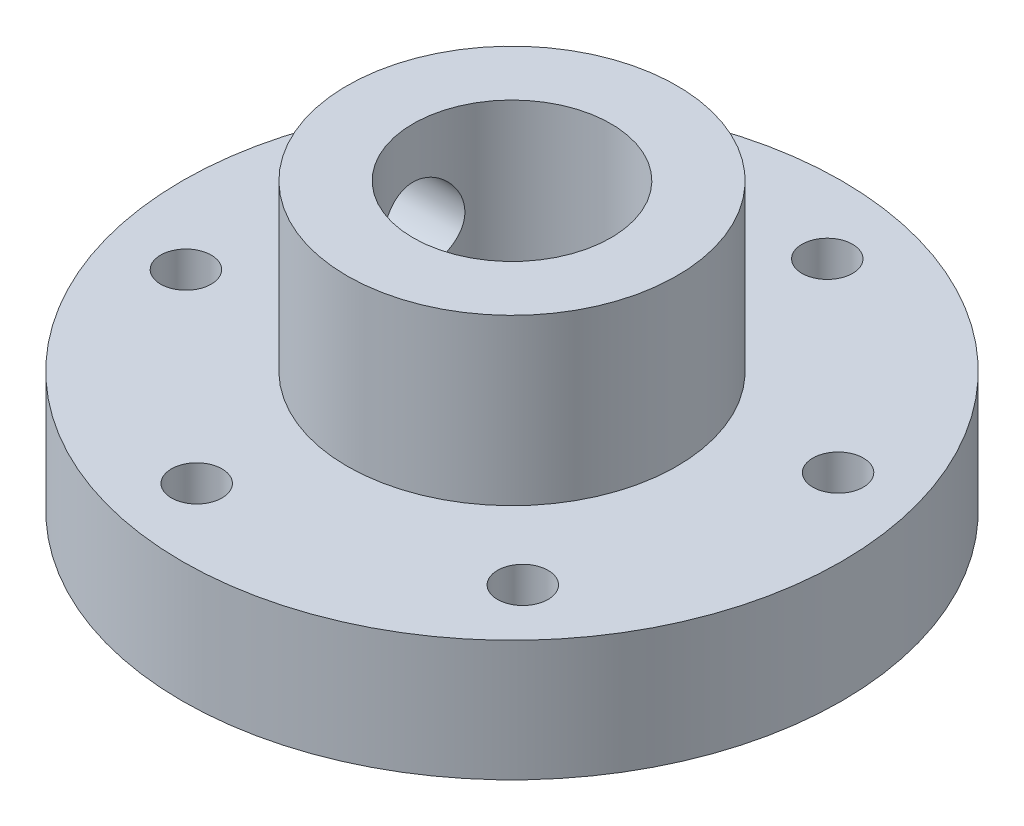
SolidWorks part; units mm, degrees
ref_plane "Front Plane" through (0, 0, 0) normal (0, 0, 1) x (1, 0, 0)
ref_plane "Top Plane" through (0, 0, 0) normal (0, 1, 0) x (1, 0, 0)
ref_plane "Right Plane" through (0, 0, 0) normal (1, 0, 0) x (0, 0, -1)
sketch "Sketch1" plane through (0, 0, 0) normal (0, 1, 0) x (1, 0, 0)
  circle A0 centre (0, 0) radius 30
  dimension "D1" = 60
sketch "Sketch2" plane through (0, 0, 0) normal (0, 1, 0) x (1, 0, 0)
  circle A0 centre (0, 0) radius 15
  dimension "D1" = 30
extrude "Boss-Extrude1" add sketch "Sketch2" along normal blind 26 contours A0
extrude "Boss-Extrude2" add sketch "Sketch1" along normal blind 11 contours A0
sketch "Sketch3" plane through (0, 26, 0) normal (0, 1, 0) x (1, 0, 0)
  circle A0 centre (0, 0) radius 9
  dimension "D1" = 18
extrude "Cut-Extrude1" cut sketch "Sketch3" against normal through all
sketch "Sketch4" plane through (0, 11, 0) normal (0, 1, 0) x (1, 0, 0)
  circle A0 centre (5.495, 23.1924) radius 2.3
  dimension "D1" = 4.6
sketch "Sketch6" plane through (0, 11, 0) normal (0, 1, 0) x (1, 0, 0)
  line L0 (-30, 0) -> (30, 0) construction
  circle A0 centre (0, 0) radius 30 construction
extrude "Cut-Extrude2" cut sketch "Sketch4" against normal through all
pattern_circular "CirPattern1" count 6 over 360 about axis through (0, 0, 0) along (0, 1, 0) of "Cut-Extrude2"
sketch "Sketch7" plane through (0, 0, 0) normal (1, 0, 0) x (0, 0, -1)
  line L0 (15, 26) -> (-15, 26) construction
  circle A0 centre (0, 17.55) radius 3.85
  dimension "D1" = 7.7
  dimension "D2" = 8.45
extrude "Cut-Extrude3" cut sketch "Sketch7" against normal up to next
